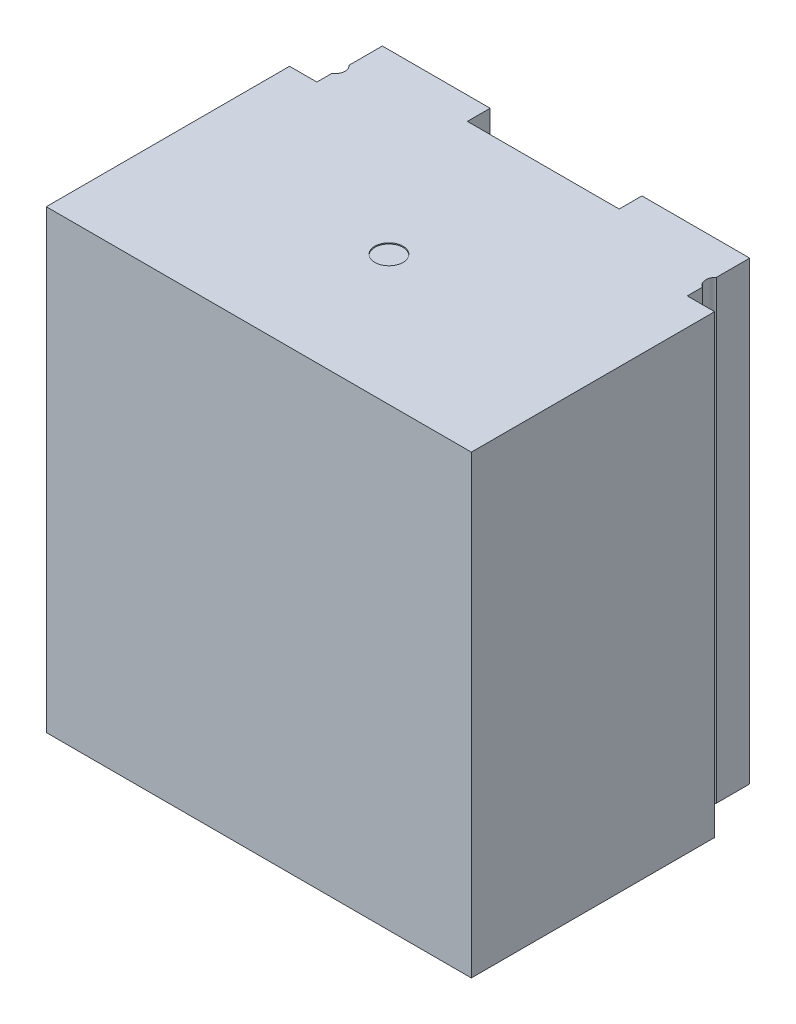
SolidWorks part; units mm, degrees
ref_plane "Front Plane" through (0, 0, 0) normal (0, 0, 1) x (1, 0, 0)
ref_plane "Top Plane" through (0, 0, 0) normal (0, 1, 0) x (1, 0, 0)
ref_plane "Right Plane" through (0, 0, 0) normal (1, 0, 0) x (0, 0, -1)
sketch "Sketch1" plane through (0, 0, 0) normal (0, 1, 0) x (1, 0, 0)
  line L0 (0, 0) -> (0, 56)
  line L1 (0, -55) -> (0, 55) construction
  line L2 (0, 0) -> (142.24, 0)
  line L3 (-55, 0) -> (55, 0) construction
  line L4 (142.24, 0) -> (142.24, 56)
  line L5 (142.24, 56) -> (133.096, 56)
  line L6 (133.096, 56) -> (133.096, 61.08)
  line L7 (132.588, 66.2246) -> (132.588, 77.4006)
  line L8 (132.588, 77.4006) -> (96.52, 77.4006)
  line L9 (96.52, 77.4006) -> (96.52, 69.7806)
  line L10 (96.52, 69.7806) -> (45.72, 69.7806)
  line L11 (45.72, 69.7806) -> (45.72, 77.4006)
  line L12 (45.72, 77.4006) -> (9.652, 77.4006)
  line L13 (9.652, 77.4006) -> (9.652, 66.2246)
  line L14 (0, 56) -> (9.144, 56)
  line L15 (9.144, 56) -> (9.144, 61.08)
  line L16 (9.652, 66.2246) -> (7.5632, 63.8335) construction
  line L17 (7.5632, 63.8335) -> (9.144, 61.08) construction
  line L18 (132.588, 66.2246) -> (134.6768, 63.8335) construction
  line L19 (134.6768, 63.8335) -> (133.096, 61.08) construction
  arc A0 (133.096, 61.08) -> (132.588, 66.2246) centre (134.6768, 63.8335) cw
  arc A1 (9.144, 61.08) -> (9.652, 66.2246) centre (7.5632, 63.8335) ccw
  dimension "D2" = 3.175
  dimension "D1" = 50.8
  dimension "D3" = 36.068
  dimension "D4" = 11.176
  dimension "D5" = 0.508
  dimension "D6" = 0.508
  dimension "D7" = 109
  dimension "D8" = 5.08
  dimension "D9" = 142.24
  dimension "D10" = 56
  dimension "D11" = 7.62
extrude "Boss-Extrude1" add sketch "Sketch1" along normal blind 152.4
scale "Scale1" scale about centroid uniform scaling yes scale factor 0.7
sketch "Sketch2" plane through (0, 0, -10.871) normal (0, 0, 1) x (1, 0, 0)
  line L1 (21.336, 22.86) -> (120.904, 22.86)
  line L2 (21.336, 22.86) -> (21.336, 129.54)
  line L3 (21.336, 129.54) -> (120.904, 129.54)
  line L4 (120.904, 22.86) -> (120.904, 129.54)
extrude "Boss-Extrude2" add sketch "Sketch2" along normal blind 17.78
sketch "Sketch3" plane through (0, 129.54, 0) normal (0, -1, 0) x (1, 0, 0)
  line L0 (21.336, 6.909) -> (120.904, 6.909) construction
  line L3 (88.9, -59.7174) -> (53.34, -59.7174) construction
  circle A0 centre (71.12, -23.571) radius 3.302
  point P6 (71.12, -59.7174)
  dimension "D2" = 6.604
  dimension "D1" = 30.48
extrude "Cut-Extrude1" cut sketch "Sketch3" along normal blind 0.254
